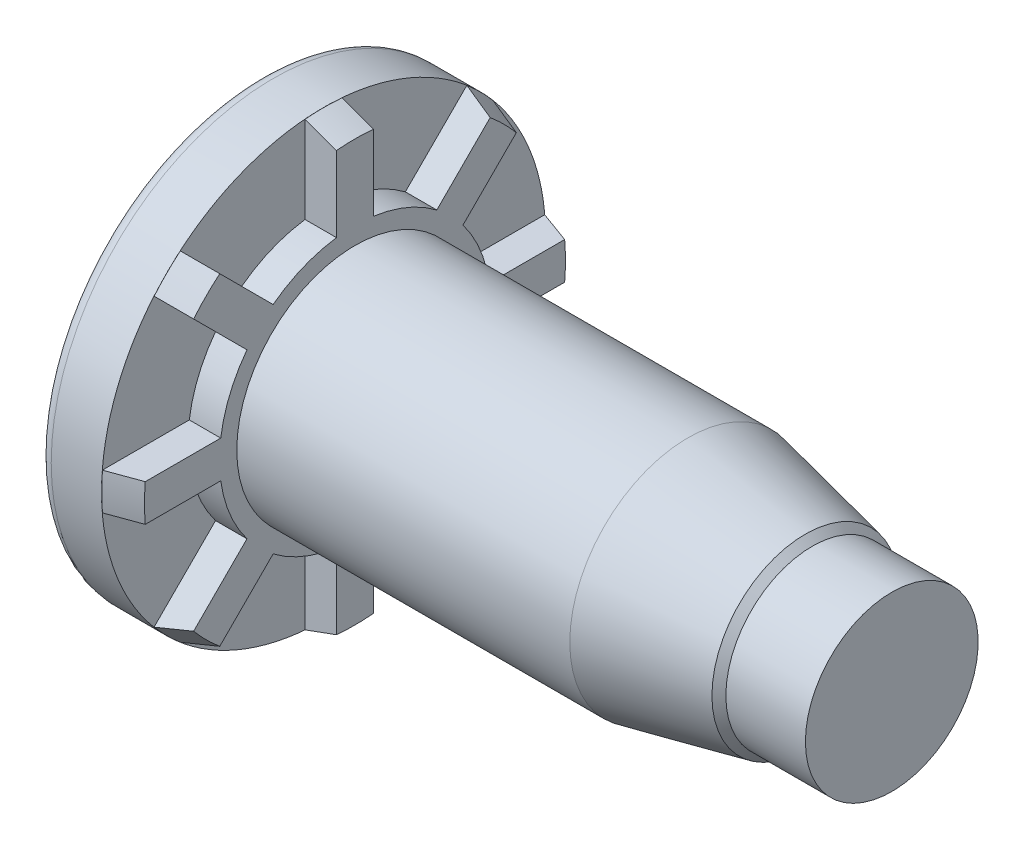
SolidWorks part; units mm, degrees
revolve "BaseBody" add sketch "BodySke" angle 360 about L6
sketch "BodySke" plane through (0, 0, 0) normal (0, 0, 1) x (1, 0, 0)
  line L0 (-2.1082, 7.0206) -> (-2.1082, 0)
  line L1 (1.0541, 7.0569) -> (1.0541, 3.9624)
  line L2 (0.0025, 7.4397) -> (1.0541, 7.0569)
  line L3 (1.0541, 3.9624) -> (12.2174, 3.9624)
  line L4 (12.2174, 3.9624) -> (16.1493, 3.1293)
  line L5 (19.05, 0) -> (-2.1082, 0)
  line L6 (0, 0) -> (50.554, 0) construction
  line L7 (16.383, 2.8956) -> (19.05, 2.8956)
  line L8 (16.383, 2.8956) -> (16.1493, 3.1293)
  line L9 (-1.6866, 7.4422) -> (0, 7.4422)
  line L10 (0.0025, 7.4397) -> (0, 7.4397)
  line L11 (1.4097, 19.05) -> (1.4097, -3.175) construction
  line L12 (0, 7.4397) -> (0, 7.4422)
  line L13 (19.05, 2.8956) -> (19.05, 0)
  arc A0 (-2.1082, 7.0206) -> (-1.6866, 7.4422) centre (-1.6866, 7.0206) cw
  dimension "Fillet_rad" = 0.4216
  dimension "T_dim" = 2.1082
  dimension "H_dia" = 14.8844
  dimension "D2" = 0.0025
  dimension "D3" = 0.0025
  dimension "Advance" = 1.4097
  dimension "D1" = 20
  dimension "Clinch_ht" = 1.0541
  dimension "Dog_len" = 2.667
  dimension "Length" = 19.05
  dimension "Dog_dia" = 5.7912
  dimension "D4" = 45
  dimension "Diameter" = 7.9248
  dimension "Thread_trans" = 4.1656
  dimension "Minor_dia" = 6.2586
cosmetic thread "ThreadCosmetic" [suppressed] parameters "Thread_length"=12.2123, "Thread_minor"=6.2586
ref_plane "Plane1" through (0, 0, 0) normal (0, 0, 1) x (1, 0, 0)
ref_plane "Plane2" through (0, 0, 0) normal (0, 1, 0) x (1, 0, 0)
ref_plane "Plane3" through (0, 0, 0) normal (1, 0, 0) x (0, 0, -1)
sketch "ThdSchSke" plane through (0, 0, 0) normal (0, 0, 1) x (1, 0, 0)
  line L0 (3.937, -3.1293) -> (3.3536, -3.9624)
  line L1 (3.937, -3.1293) -> (4.5204, -3.9624)
  line L2 (4.5204, -3.9624) -> (4.5204, -4.953)
  line L3 (-3.175, 0) -> (5.1513, 0) construction
  line L4 (0, -7.4422) -> (0, 7.4422) construction
  line L5 (4.5204, -4.953) -> (3.3536, -4.953)
  line L6 (3.3536, -4.953) -> (3.3536, -3.9624)
  line L7 (21.9888, 6.5809) -> (21.9888, 1.1961) construction
  dimension "Diameter" = 7.9248
  dimension "Thread_minor" = 6.2586
  dimension "Start" = 3.937
revolve "ThreadSchematic" [suppressed] cut sketch "ThdSchSke" angle 360 about L3
pattern_linear "ThdSchPat" [suppressed]
sketch "RibCutSke" plane through (1.0541, 1.7944, -0.091) normal (1, 0, 0) x (0, 0, -1)
  line L0 (0.5289, 2.7055) -> (0.5289, 5.6219)
  line L1 (2.6526, 1.8258) -> (4.7149, 3.888)
  line L2 (0.5289, 2.1192) -> (0.5289, 2.4006) construction
  line L3 (-0.091, -1.7944) -> (-0.091, 5.0239) construction
  line L4 (-0.091, -1.7944) -> (0.5289, 2.1192) construction
  line L5 (-0.091, -1.7944) -> (2.2381, 1.4112) construction
  line L6 (2.2381, 1.4112) -> (2.4421, 1.6153) construction
  arc A1 (2.6526, 1.8258) -> (0.5289, 2.7055) centre (-0.091, -1.7944) ccw
  arc A2 (4.7149, 3.888) -> (0.5289, 5.6219) centre (-0.091, -1.7944) ccw
  circle A3 centre (-0.091, -1.7944) radius 7.0569 construction
  circle A4 centre (-0.091, -1.7944) radius 3.9624 construction
  dimension "Rib_root_half_angle" = 9
  dimension "Rib_root_gap_angle" = 27
  dimension "Angle" = 45
extrude "RibCut" cut sketch "RibCutSke" against normal blind 1.0541
pattern_circular "RibCutsPat" count 8 every 45 about axis through (0, 0, 0) along (1, 0, 0) of "RibCut"
equation "' \"Length@BodySke\" = 0.75"
equation "' \"H_dia@BodySke\" = 0.586"
equation "' \"Start@ThdSchSke\" = 0.155"
equation "' \"T_dim@BodySke\" = 0.083"
equation "' \"Dog_dia@BodySke\" = 0.228"
equation "' \"Dog_len@BodySke\" = 0.105"
equation "' \"Thread_trans@BodySke\" = 0.164"
equation "' \"Diameter@BodySke\" = 0.312"
equation "' \"Minor_dia@BodySke\" =  0.2464"
equation "' \"Minor_dia@BodySke\" = 0.2464"
equation "' \"Advance@BodySke\" = 0.0555"
equation "\"Fillet_rad@BodySke\" =  \"T_dim@BodySke\" * 0.2"
equation "\"Clinch_ht@BodySke\" = \"T_dim@BodySke\" * 0.5"
equation "\"Num_ribs@RibCutsPat\" = 8"
equation "\"Angle@RibCutSke\" =\"Angle@RibCutsPat\""
equation "\"Rib_root_half_angle@RibCutSke\" = \"Angle@RibCutSke\" / 5"
equation "\"Rib_root_gap_angle@RibCutSke\" = \"Angle@RibCutSke\" - (2 * \"Rib_root_half_angle@RibCutSke\" )"
equation "\"Rib_root_dia@RibCutSke\" = \"Diameter@BodySke\""
equation "\"Inner_dia@RibCutSke\" = \"Diameter@BodySke\" + ( \"H_dia@BodySke\" - \"Diameter@BodySke\" ) / 6"
equation "\"Outer_dia@RibCutSke\" = \"H_dia@BodySke\""
equation "\"Depth@RibCut\" = \"Clinch_ht@BodySke\""
equation "\"Thread_length@ThreadCosmetic\" = \"Length@BodySke\" - \"Start@ThdSchSke\"  - \"Dog_len@BodySke\"  - ( \"Minor_dia@BodySke\" - \"Dog_dia@BodySke\" ) / 2"
equation "\"Thread_minor@ThreadCosmetic\" = \"Minor_dia@BodySke\""
equation "\"Thread_minor@ThdSchSke\" = \"Minor_dia@BodySke\""
equation "\"Diameter@ThdSchSke\" = \"Diameter@BodySke\""
equation "\"Overcut@ThdSchSke\" = \"Diameter@BodySke\" * 1.25"
equation "\"Num_threads@ThdSchPat\" = int( \"Thread_length@ThreadCosmetic\" / \"Advance@BodySke\" + 0.999 )  + 1"
equation "\"Advance@ThdSchPat\" = \"Thread_length@ThreadCosmetic\" /  (\"Num_threads@ThdSchPat\" - 1) 'relax it"
equation "\"Num_threads@ThdSchPat\" = \"Num_threads@ThdSchPat\" - sgn( \"Num_threads@ThdSchPat\" - 1) '---chamfered tips only---"
